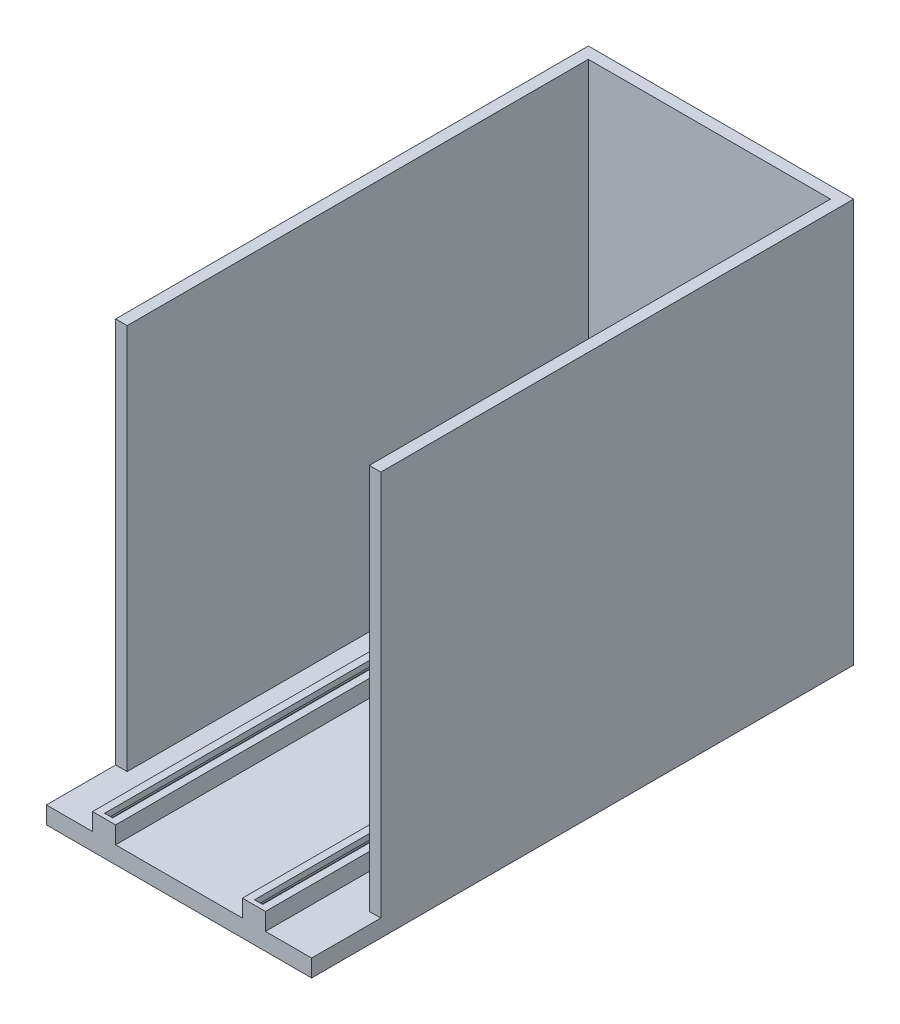
SolidWorks part; units mm, degrees
ref_plane "Front Plane" through (0, 0, 0) normal (0, 0, 1) x (1, 0, 0)
ref_plane "Top Plane" through (0, 0, 0) normal (0, 1, 0) x (1, 0, 0)
ref_plane "Right Plane" through (0, 0, 0) normal (1, 0, 0) x (0, 0, -1)
sketch "Sketch1" plane through (0, 0, 0) normal (0, 1, 0) x (1, 0, 0)
  line L1 (-146.05, -298.45) -> (146.05, -298.45)
  line L2 (-146.05, -298.45) -> (-146.05, 298.45)
  line L3 (-146.05, 298.45) -> (146.05, 298.45)
  line L4 (146.05, -298.45) -> (146.05, 298.45)
  line L5 (-146.05, -298.45) -> (146.05, 298.45) construction
  line L6 (-146.05, 298.45) -> (146.05, -298.45) construction
  point P0 (0, 0)
  dimension "D1" = 596.9
  dimension "D2" = 292.1
extrude "Boss-Extrude1" add sketch "Sketch1" along normal blind 19.05
sketch "Sketch2" plane through (0, 19.05, 0) normal (0, 1, 0) x (1, 0, 0)
  line L0 (-146.05, -222.25) -> (-146.05, 298.45)
  line L1 (-146.05, 298.45) -> (-146.05, -298.45) construction
  line L2 (-146.05, 298.45) -> (146.05, 298.45)
  line L3 (146.05, 298.45) -> (-146.05, 298.45) construction
  line L4 (146.05, -298.45) -> (146.05, 298.45) construction
  line L5 (146.05, 298.45) -> (146.05, -222.25)
  line L6 (146.05, -222.25) -> (133.35, -222.25)
  line L7 (133.35, -222.25) -> (133.35, 285.75)
  line L8 (133.35, 285.75) -> (-133.35, 285.75)
  line L9 (-133.35, 285.75) -> (-133.35, -222.25)
  line L10 (-133.35, -222.25) -> (-146.05, -222.25)
  dimension "D1" = 76.2
  dimension "D2" = 12.7
  dimension "D3" = 12.7
extrude "Boss-Extrude2" add sketch "Sketch2" along normal blind 425.45
sketch "Sketch3" plane through (0, 19.05, 0) normal (0, 1, 0) x (1, 0, 0)
  line L0 (-69.85, -298.45) -> (-69.85, 209.55)
  line L3 (-146.05, -298.45) -> (146.05, -298.45) construction
  line L4 (-69.85, 209.55) -> (-95.25, 209.55)
  line L5 (-95.25, 209.55) -> (-95.25, -298.45)
  line L6 (-95.25, -298.45) -> (-69.85, -298.45)
  dimension "D1" = 508
  dimension "D2" = 25.4
  dimension "D3" = 50.8
extrude "Boss-Extrude3" add sketch "Sketch3" along normal blind 7.62
sketch "Sketch4" plane through (0, 26.67, 0) normal (0, 1, 0) x (1, 0, 0)
  line L0 (-90.17, 204.47) -> (-90.17, -293.37)
  line L1 (-69.85, 209.55) -> (-95.25, 209.55) construction
  line L2 (-95.25, -298.45) -> (-69.85, -298.45) construction
  line L3 (-95.25, -298.45) -> (-69.85, -298.45)
  line L4 (-95.25, -298.45) -> (-95.25, 209.55)
  line L5 (-95.25, 209.55) -> (-69.85, 209.55)
  line L6 (-82.55, 209.55) -> (-82.55, -298.45) construction
  line L7 (-74.93, -293.37) -> (-90.17, -293.37)
  line L8 (-90.17, 204.47) -> (-74.93, 204.47)
  line L9 (-69.85, -298.45) -> (-69.85, 209.55)
  line L10 (-74.93, 204.47) -> (-74.93, -293.37)
  point P16 (-74.93, 204.47)
  dimension "D1" = 5.08
  dimension "D2" = 5.08
  dimension "D3" = 5.08
  dimension "D4" = 5.08
  dimension "D5" = 5.08
extrude "Boss-Extrude4" add sketch "Sketch4" along normal blind 11.43
sketch "Sketch5" plane through (-90.17, 0, 0) normal (1, 0, 0) x (0, 0, -1)
  line L0 (-293.37, 38.1) -> (204.47, 38.1)
  line L2 (204.47, 38.1) -> (204.47, 31.75)
  line L3 (204.47, 38.1) -> (204.47, 26.67) construction
  line L4 (204.47, 31.75) -> (-293.37, 31.75)
  line L6 (-293.37, 31.75) -> (-293.37, 38.1)
  point P5 (0, 0)
  dimension "D1" = 6.35
extrude "Boss-Extrude5" add sketch "Sketch5" along normal blind 3.175
ref_plane "Plane1" through (-82.55, 0, 0) normal (1, 0, 0) x (0, 0, -1)
mirror "Mirror1" about plane through (-82.55, 0, 0) normal (1, 0, 0) of "Boss-Extrude5"
mirror "Mirror2" about plane through (0, 0, 0) normal (1, 0, 0) of "Boss-Extrude4", "Mirror1", "Boss-Extrude5", "Boss-Extrude3", "Boss-Extrude1"
